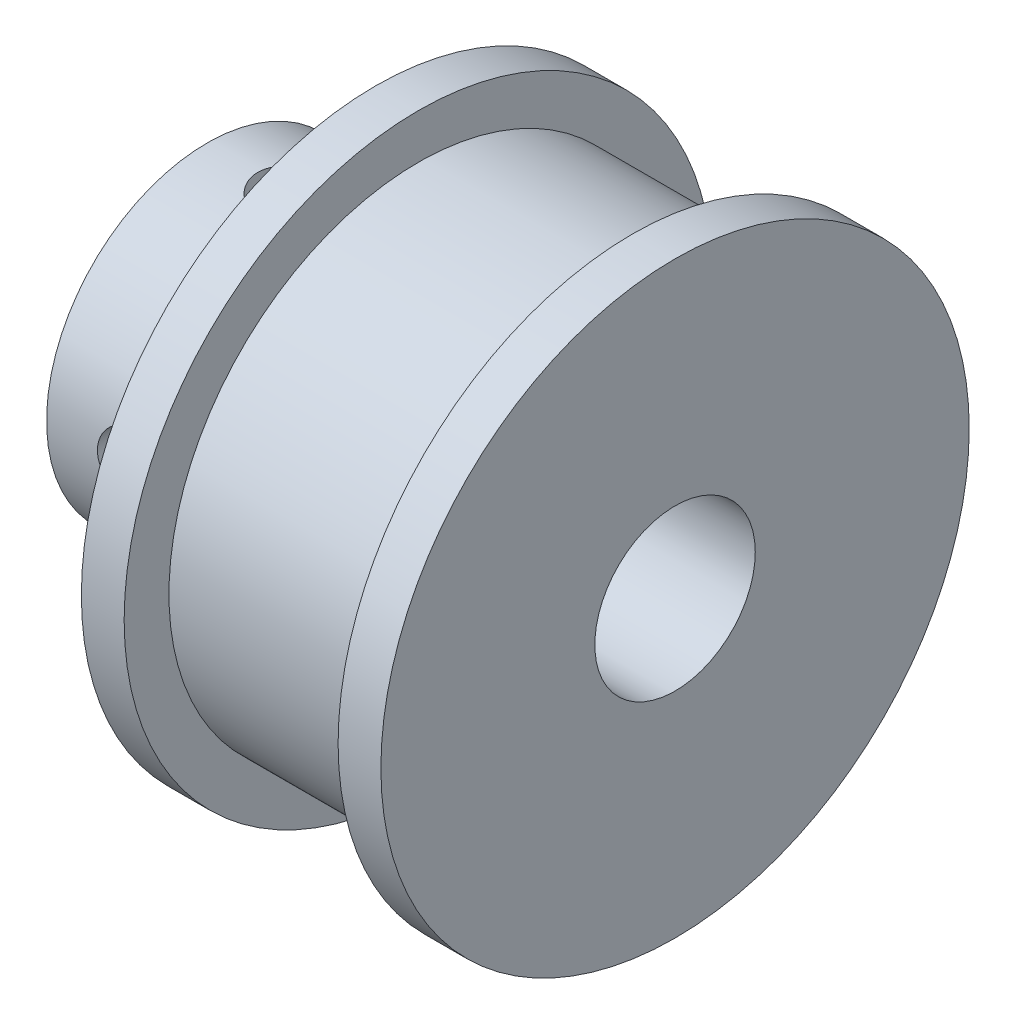
SolidWorks part; units mm, degrees
material "6061-T6 (SS)"
ref_plane "Front Plane" through (0, 0, 0) normal (0, 0, 1) x (1, 0, 0)
ref_plane "Top Plane" through (0, 0, 0) normal (0, 1, 0) x (1, 0, 0)
ref_plane "Right Plane" through (0, 0, 0) normal (1, 0, 0) x (0, 0, -1)
sketch "Sketch1" plane through (0, 0, 0) normal (0, 0, 1) x (1, 0, 0)
  line L0 (0, 2.5) -> (0, 6)
  line L1 (6.3, 11) -> (7.9, 11)
  line L2 (7.9, 11) -> (7.9, 9.325)
  line L3 (7.9, 9.325) -> (15.9, 9.325)
  line L4 (15.9, 9.325) -> (15.9, 11)
  line L5 (15.9, 11) -> (17.5, 11)
  line L6 (17.5, 11) -> (17.5, 2.5)
  line L7 (17.5, 2.5) -> (0, 2.5)
  line L8 (0, 0) -> (-7.6744, 0) construction
  line L9 (6.3, 11) -> (6.3, 6)
  line L10 (6.3, 6) -> (0, 6)
  dimension "D1" = 5
  dimension "D2" = 22
  dimension "D3" = 18.65
  dimension "D4" = 11.2
  dimension "D5" = 17.5
  dimension "D6" = 1.6
  dimension "D7" = 12
revolve "Revolve1" add sketch "Sketch1" angle 360 about L8
hole_wizard "M3x0.5 Tapped Hole1" positions "Sketch3" profile "Sketch2" tap size "M3x0.5" standard "ANSI Metric"
sketch "Sketch3" plane through (0, 0, 0) normal (0, 1, 0) x (1, 0, 0)
  line L0 (0, 0) -> (6.3, 0) construction
  line L2 (6.3, 6) -> (6.3, -6) construction
  point P8 (3.15, 0)
sketch "Sketch2" plane through (3.15, 0, 0) normal (1, 0, 0) x (0, 0, -1)
  line L0 (0, 0) -> (0, 11)
  line L1 (0, 11) -> (1.25, 11)
  line L2 (1.25, 11) -> (1.25, 0)
  line L5 (1.25, 0) -> (0, 0)
  line L11 (0, -6.35) -> (0, 107.95) construction
  dimension "Thread Major Dia." = 2.5
  dimension "Thru Tap Drill Depth" = 11
hole_wizard "M3x0.5 Tapped Hole2" positions "Sketch5" profile "Sketch4" tap size "M3x0.5" standard "ANSI Metric"
sketch "Sketch5" plane through (0, 0, 0) normal (0, 0, 1) x (1, 0, 0)
  line L0 (0, 0) -> (6.3, 0) construction
  line L2 (6.3, 11) -> (6.3, -11) construction
  point P7 (3.15, 0)
sketch "Sketch4" plane through (3.15, 0, 0) normal (1, 0, 0) x (0, 1, 0)
  line L0 (0, 0) -> (0, 11)
  line L1 (0, 11) -> (1.25, 11)
  line L2 (1.25, 11) -> (1.25, 0)
  line L5 (1.25, 0) -> (0, 0)
  line L11 (0, -6.35) -> (0, 107.95) construction
  dimension "Thread Major Dia." = 2.5
  dimension "Thru Tap Drill Depth" = 11
sketch "Sketch6" plane through (17.5, 0, 0) normal (1, 0, 0) x (0, 0, -1)
  circle A0 centre (0, 0) radius 3
extrude "Cut-Extrude1" cut sketch "Sketch6" against normal through all
